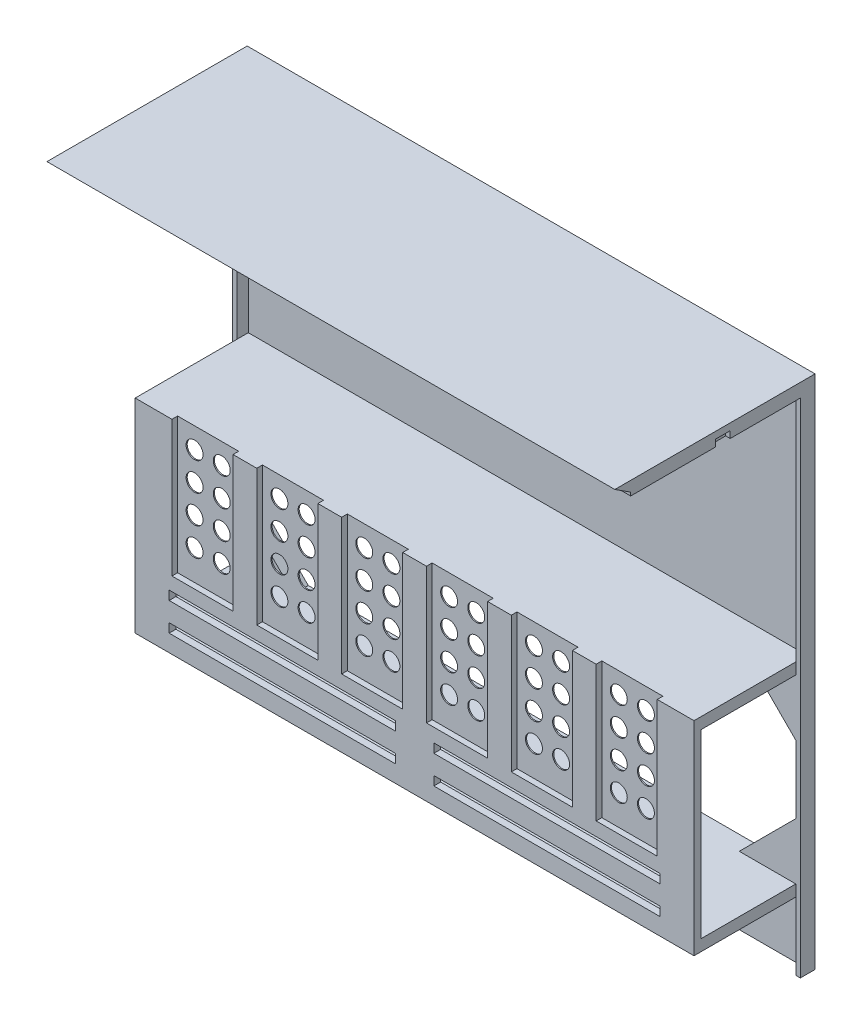
SolidWorks part; units mm, degrees
ref_plane "前视基准面" through (0, 0, 0) normal (0, 0, 1) x (1, 0, 0)
ref_plane "上视基准面" through (0, 0, 0) normal (0, 1, 0) x (1, 0, 0)
ref_plane "右视基准面" through (0, 0, 0) normal (1, 0, 0) x (0, 0, -1)
other "Configuration Table"
sketch "Sketch1" plane through (0, 0, 0) normal (0, 0, 1) x (1, 0, 0)
  line L16 (-13.0072, 0) -> (-13.0072, 90)
  line L17 (-13.0072, 90) -> (85.7928, 90)
  line L18 (85.7928, 90) -> (85.7928, 0)
  line L19 (85.7928, 0) -> (86.5928, 0)
  line L20 (86.5928, 0) -> (86.5928, 91.2)
  line L21 (86.5928, 91.2) -> (-13.8072, 91.2)
  line L22 (-13.8072, 91.2) -> (-13.8072, 0)
  line L23 (-13.8072, 0) -> (-13.0072, 0)
extrude "Boss-Extrude1" add sketch "Sketch1" along normal blind 2.6
sketch "Sketch2" plane through (0, 0, 2.6) normal (0, 0, 1) x (1, 0, 0)
  line L0 (86.5928, 0) -> (86.5928, 91.2) construction
  line L1 (-13.8072, 91.2) -> (86.5928, 91.2)
  line L2 (-13.8072, 91.2) -> (-13.8072, 88.8)
  line L3 (-13.8072, 88.8) -> (86.5928, 88.8)
  line L4 (86.5928, 91.2) -> (86.5928, 88.8)
  dimension "D1" = 2.4
extrude "Boss-Extrude2" add sketch "Sketch2" along normal blind 30
pattern_linear "LPattern1" count 2 spacing 15 along (0, 0, 1) of "Boss-Extrude1"
sketch "Sketch5" plane through (85.7928, 0, 0) normal (-1, 0, 0) x (0, 0, 1)
  line L0 (17.6, 88.8) -> (17.6, 0) construction
  line L3 (20.6, 48) -> (5.6, 48)
  line L5 (15, 88.8) -> (15, 0) construction
  line L7 (20.6, 12) -> (0.6, 12)
  line L8 (15, 90) -> (15.6, 90)
  line L14 (15.6, 0) -> (15, 0)
  line L20 (20.6, 12) -> (20.6, 48)
  line L21 (20.6, 48) -> (0.6, 48)
  line L22 (0, 12.0761) -> (0, 48.0761)
  line L23 (0, 90) -> (0.6, 90)
  line L24 (0, 90) -> (0, 48.0761)
  line L25 (0.6, 90) -> (0.6, 48)
  line L26 (0.6, 12) -> (0.6, 0)
  line L27 (0.6, 0) -> (0, 0)
  line L28 (0, 12.0761) -> (0, 0)
  line L33 (0, 90) -> (0, 0) construction
  line L34 (2.6, 90) -> (0, 90) construction
  line L35 (2.6, 0) -> (0, 0) construction
  line L36 (20.6, 12) -> (5.6, 12)
  line L37 (19.4, 46) -> (0.6, 46)
  line L38 (19.4, 46) -> (19.4, 14)
  line L39 (19.4, 14) -> (0.6, 14)
  line L40 (0.6, 46) -> (0.6, 14)
  line M7 (15, 88.8) -> (15, 0)
  line M9 (17.6, 0) -> (17.6, 88.8)
  dimension "D2" = 0
  dimension "D3" = 3
  dimension "D4" = 0.6
  dimension "D5" = 2
  dimension "D6" = 2
  dimension "D7" = 1.2
  dimension "D8" = 0
  dimension "D10" = 0.6
  dimension "D11" = 36
  dimension "D12" = 12
  dimension "D13" = 20
extrude "Boss-Extrude4" add sketch "Sketch5" along normal up to surface (98.8 mm away) contours L38 L39 L7 L20 L3 L37 M9 | L40 L37 L3 L21 L25 L23 L24 L22 L28 L27 L26 L7 L39 M7 | L39 L7 M9 M7 | L37 L3 M9 M7 up to face at (-13.0072, 44.4, 16.3)
sketch "Sketch7" plane through (0, 0, 0) normal (0, -1, 0) x (1, 0, 0)
  line L1 (-13.8072, 17.6) -> (-13.0072, 17.6)
  line L2 (-13.8072, 17.6) -> (-13.8072, 15)
  line L3 (-13.8072, 15) -> (-13.0072, 15)
  line L4 (-13.0072, 17.6) -> (-13.0072, 15)
extrude "Cut-Extrude1" cut sketch "Sketch7" against normal up to surface (90 mm away) up to face at (36.3928, 90, 1.6)
sketch "Sketch8" plane through (0, 0, 0) normal (0, -1, 0) x (1, 0, 0)
  line L1 (85.7928, 17.6) -> (86.5928, 17.6)
  line L2 (85.7928, 17.6) -> (85.7928, 15)
  line L3 (85.7928, 15) -> (86.5928, 15)
  line L4 (86.5928, 17.6) -> (86.5928, 15)
extrude "Cut-Extrude2" cut sketch "Sketch8" against normal up to surface (90 mm away) up to face at (36.3928, 90, 1.6)
sketch "Sketch10" plane through (86.5928, 0, 0) normal (1, 0, 0) x (0, 0, -1)
  line L0 (-32.6, 88.8) -> (-32.6, 91.2) construction
  line L1 (-35.4, 91.2) -> (-32.6, 89.4)
  line L3 (-32.6, 89.4) -> (-32.6, 91.2)
  line L4 (-32.6, 91.2) -> (-35.4, 91.2)
  line L6 (-32.6, 91.2) -> (0, 91.2) construction
  dimension "D1" = 2.8
  dimension "D2" = 1.8
  dimension "D3" = 0
extrude "Boss-Extrude5" add sketch "Sketch10" against normal up to surface (100.4 mm away) up to face at (-13.8072, 71.76, 13.56)
sketch "Sketch11" plane through (0, 0, 20.6) normal (0, 0, 1) x (1, 0, 0)
  line L0 (-13.0072, 48) -> (85.7928, 48) construction
  line L1 (-6.5072, 48) -> (4.2928, 48)
  line L2 (-6.5072, 48) -> (-6.5072, 24)
  line L3 (-6.5072, 24) -> (4.2928, 24)
  line L4 (4.2928, 48) -> (4.2928, 24)
  line L5 (-13.0072, 14) -> (-13.0072, 46) construction
  dimension "D1" = 10.8
  dimension "D2" = 0
  dimension "D3" = 24
  dimension "D4" = 6.5
extrude "Cut-Extrude3" cut sketch "Sketch11" against normal blind 1
pattern_linear "LPattern2" count 6 spacing 15 along (1, 0, 0) of "Cut-Extrude3"
sketch "Sketch13" plane through (0, 0, 0.6) normal (0, 0, 1) x (1, 0, 0)
  line L1 (-13.0072, 46) -> (85.7928, 46)
  line L2 (-13.0072, 46) -> (-13.0072, 14)
  line L3 (-13.0072, 14) -> (85.7928, 14)
  line L4 (85.7928, 46) -> (85.7928, 14)
extrude "Cut-Extrude4" cut sketch "Sketch13" against normal blind 10
chamfer "Chamfer1" distance 10 angle 45 4 edges at (-13.0072, 46, 1.3) (-13.0072, 14, 1.3) (85.7928, 14, 1.3) (85.7928, 46, 1.3)
sketch "Sketch15" plane through (0, 0, 19.6) normal (0, 0, 1) x (1, 0, 0)
  line L0 (-6.5072, 48) -> (-6.5072, 24) construction
  line L1 (4.2928, 24) -> (4.2928, 48) construction
  circle A6 centre (-3.5072, 44.3151) radius 1.5
  circle A7 centre (1.2928, 44.3151) radius 1.5
  circle A8 centre (11.4928, 44.3151) radius 1.5
  circle A9 centre (16.2928, 44.3151) radius 1.5
  circle A10 centre (26.4928, 44.3151) radius 1.5
  circle A11 centre (31.2928, 44.3151) radius 1.5
  circle A12 centre (41.4928, 44.3151) radius 1.5
  circle A13 centre (46.2928, 44.3151) radius 1.5
  circle A14 centre (56.4928, 44.3151) radius 1.5
  circle A15 centre (61.2928, 44.3151) radius 1.5
  circle A16 centre (71.4928, 44.3151) radius 1.5
  circle A17 centre (76.2928, 44.3151) radius 1.5
  circle A18 centre (11.4928, 39.3151) radius 1.5
  circle A19 centre (16.2928, 39.3151) radius 1.5
  circle A20 centre (26.4928, 39.3151) radius 1.5
  circle A21 centre (31.2928, 39.3151) radius 1.5
  circle A22 centre (41.4928, 39.3151) radius 1.5
  circle A23 centre (46.2928, 39.3151) radius 1.5
  circle A24 centre (56.4928, 39.3151) radius 1.5
  circle A25 centre (61.2928, 39.3151) radius 1.5
  circle A26 centre (71.4928, 39.3151) radius 1.5
  circle A27 centre (76.2928, 39.3151) radius 1.5
  circle A28 centre (11.4928, 34.3151) radius 1.5
  circle A29 centre (16.2928, 34.3151) radius 1.5
  circle A30 centre (26.4928, 34.3151) radius 1.5
  circle A31 centre (31.2928, 34.3151) radius 1.5
  circle A32 centre (41.4928, 34.3151) radius 1.5
  circle A33 centre (46.2928, 34.3151) radius 1.5
  circle A34 centre (56.4928, 34.3151) radius 1.5
  circle A35 centre (61.2928, 34.3151) radius 1.5
  circle A36 centre (71.4928, 34.3151) radius 1.5
  circle A37 centre (76.2928, 34.3151) radius 1.5
  circle A38 centre (11.4928, 29.3151) radius 1.5
  circle A39 centre (16.2928, 29.3151) radius 1.5
  circle A40 centre (26.4928, 29.3151) radius 1.5
  circle A41 centre (31.2928, 29.3151) radius 1.5
  circle A42 centre (41.4928, 29.3151) radius 1.5
  circle A43 centre (46.2928, 29.3151) radius 1.5
  circle A44 centre (56.4928, 29.3151) radius 1.5
  circle A45 centre (61.2928, 29.3151) radius 1.5
  circle A46 centre (71.4928, 29.3151) radius 1.5
  circle A47 centre (76.2928, 29.3151) radius 1.5
  circle A48 centre (-3.5072, 39.3151) radius 1.5
  circle A49 centre (1.2928, 39.3151) radius 1.5
  circle A50 centre (-3.5072, 34.3151) radius 1.5
  circle A51 centre (1.2928, 34.3151) radius 1.5
  circle A52 centre (-3.5072, 29.3151) radius 1.5
  circle A53 centre (1.2928, 29.3151) radius 1.5
  dimension "D1" = 3
  dimension "D2" = 3
  dimension "D3" = 3
  dimension "D4" = 6
  dimension "D5" = 4
extrude "Cut-Extrude17" cut sketch "Sketch15" against normal blind 10
sketch "Sketch18" plane through (0, 0, 20.6) normal (0, 0, 1) x (1, 0, 0)
  line L0 (39.7928, 21.6) -> (39.7928, 20)
  line L1 (-7.0072, 21.6) -> (32.9928, 21.6)
  line L2 (-7.0072, 21.6) -> (-7.0072, 20)
  line L3 (-7.0072, 20) -> (32.9928, 20)
  line L4 (32.9928, 21.6) -> (32.9928, 20)
  line L5 (39.7928, 21.6) -> (79.7928, 21.6)
  line L6 (79.7928, 21.6) -> (79.7928, 20)
  line L7 (39.7928, 20) -> (79.7928, 20)
  line L8 (39.7928, 16.6) -> (39.7928, 15)
  line L9 (39.7928, 16.6) -> (79.7928, 16.6)
  line L10 (79.7928, 16.6) -> (79.7928, 15)
  line L11 (39.7928, 15) -> (79.7928, 15)
  line L12 (-7.0072, 16.6) -> (-7.0072, 15)
  line L13 (-7.0072, 16.6) -> (32.9928, 16.6)
  line L14 (32.9928, 16.6) -> (32.9928, 15)
  line L15 (-7.0072, 15) -> (32.9928, 15)
  line L16 (-13.0072, 12) -> (-13.0072, 48) construction
  line L17 (85.7928, 12) -> (85.7928, 48) construction
  line L18 (23.4928, 24) -> (34.2928, 24) construction
  dimension "D1" = 1.6
  dimension "D4" = 6
  dimension "D5" = 6
  dimension "D6" = 40
  dimension "D7" = 4
  dimension "D2" = 2
  dimension "D3" = 2
extrude "Cut-Extrude18" cut sketch "Sketch18" against normal blind 10
